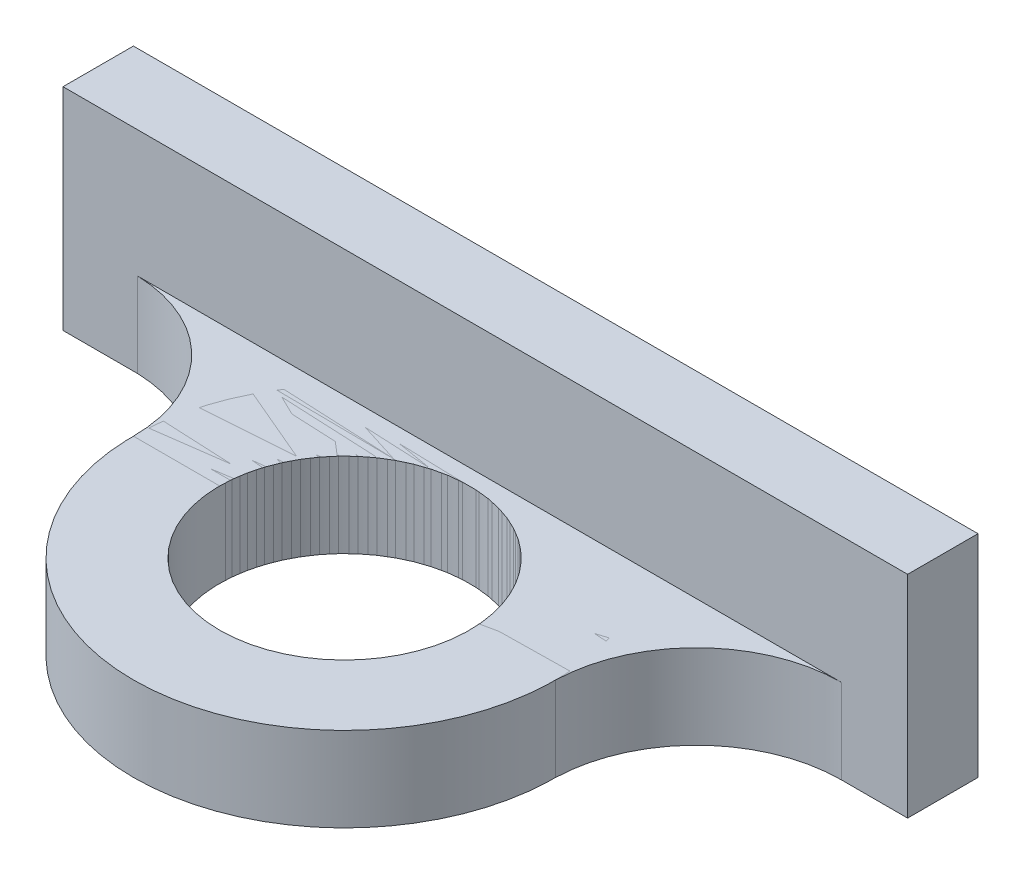
SolidWorks part; units mm, degrees
ref_plane "Front Plane" through (0, 0, 0) normal (0, 0, 1) x (1, 0, 0)
ref_plane "Top Plane" through (0, 0, 0) normal (0, 1, 0) x (1, 0, 0)
ref_plane "Right Plane" through (0, 0, 0) normal (1, 0, 0) x (0, 0, -1)
sketch "Sketch1" plane through (0, 0, 0) normal (0, 1, 0) x (1, 0, 0)
  circle A0 centre (0, 0) radius 17.75
  circle A1 centre (0, 0) radius 30
  point P0 (0, 0)
  dimension "D2" = 35.5
  dimension "D1" = 60
extrude "Boss-Extrude1" add sketch "Sketch1" along normal blind 12
sketch "Sketch5" plane through (0, 0, 0) normal (0, -1, 0) x (1, 0, 0)
  line L1 (0, -30) -> (60, -30)
  line L4 (60, -30) -> (60, -20)
  line L5 (0, -30) -> (-60, -30)
  line L6 (60, -20) -> (0, -20)
  line L7 (0, -20) -> (-60, -20)
  line L8 (-60, -30) -> (-60, -20)
  circle A0 centre (0, 0) radius 30 construction
  point P3 (0, -30)
  point P15 (0, 0)
  dimension "D2" = 60
  dimension "D3" = 10
  dimension "D4" = 60
extrude "Boss-Extrude2" add sketch "Sketch5" against normal blind 30
sketch "Sketch6" plane through (0, 0, 0) normal (0, -1, 0) x (1, 0, 0)
  line L0 (-50.5902, -20) -> (50.5902, -20)
  line L2 (-30, 0) -> (-17.75, 0)
  line L5 (30, 0) -> (17.75, 0)
  arc A0 (22.3607, -20) -> (-22.3607, -20) centre (0, 0) ccw construction
  arc A1 (-30, 0) -> (-50.5902, -20) centre (-50.0085, 0) cw
  circle A2 centre (0, 0) radius 17.75 construction
  arc A3 (50.5902, -20) -> (30, 0) centre (50.5902, 0.5989) cw
  arc A4 (-17.75, 0) -> (17.75, 0) centre (0, 0) ccw
  point P19 (0, 0)
  arc M1 (22.3607, -20) -> (-22.3607, -20) centre (0, 0) ccw
  line M2 (-22.3607, -20) -> (-60, -20)
  line M6 (60, -20) -> (22.3607, -20)
  circle M7 centre (0, 0) radius 17.75
extrude "Boss-Extrude3" add sketch "Sketch6" against normal blind 12 separate body contours L5 L2 L0 M1 M7 | A3 M6 M1 | A1 M1 M2
ref_point "Point1"
sketch "Alignment Sketch" plane through (0, 0, -30) normal (0, 0, -1) x (-1, 0, 0)
  line L0 (60, 15) -> (-60, 15) construction
  line L1 (60, 30) -> (60, 0) construction
  line L2 (-60, 30) -> (-60, 0) construction
  line L3 (0, 0) -> (0, 30) construction
  line L4 (60, 30) -> (-60, 30) construction
